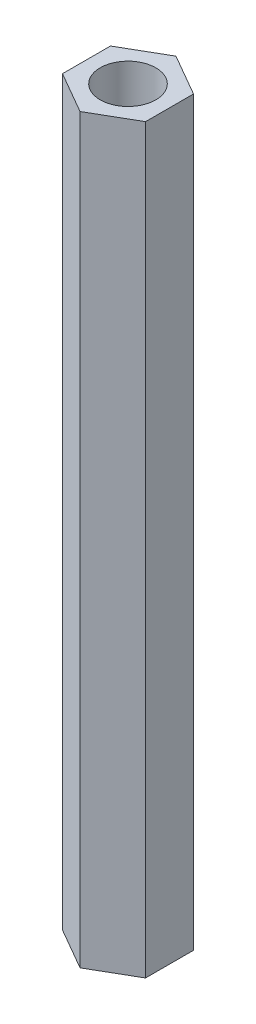
SolidWorks part; units mm, degrees
ref_plane "Front Plane" through (0, 0, 0) normal (0, 0, 1) x (1, 0, 0)
ref_plane "Top Plane" through (0, 0, 0) normal (0, 1, 0) x (1, 0, 0)
ref_plane "Right Plane" through (0, 0, 0) normal (1, 0, 0) x (0, 0, -1)
sketch "Sketch1" plane through (0, 0, 0) normal (0, 1, 0) x (1, 0, 0)
  line L1 (0, -2.0531) -> (1.778, -1.0265)
  line L2 (1.778, -1.0265) -> (1.778, 1.0265)
  line L3 (1.778, 1.0265) -> (0, 2.0531)
  line L4 (0, 2.0531) -> (-1.778, 1.0265)
  line L5 (-1.778, 1.0265) -> (-1.778, -1.0265)
  line L6 (-1.778, -1.0265) -> (0, -2.0531)
  circle A0 centre (0, 0) radius 1.778 construction
  circle A1 centre (0, 0) radius 1.1906
  dimension "D1" = 2.3813
  dimension "D2" = 1.778
extrude "Boss-Extrude1" add sketch "Sketch1" along normal blind 31.75
